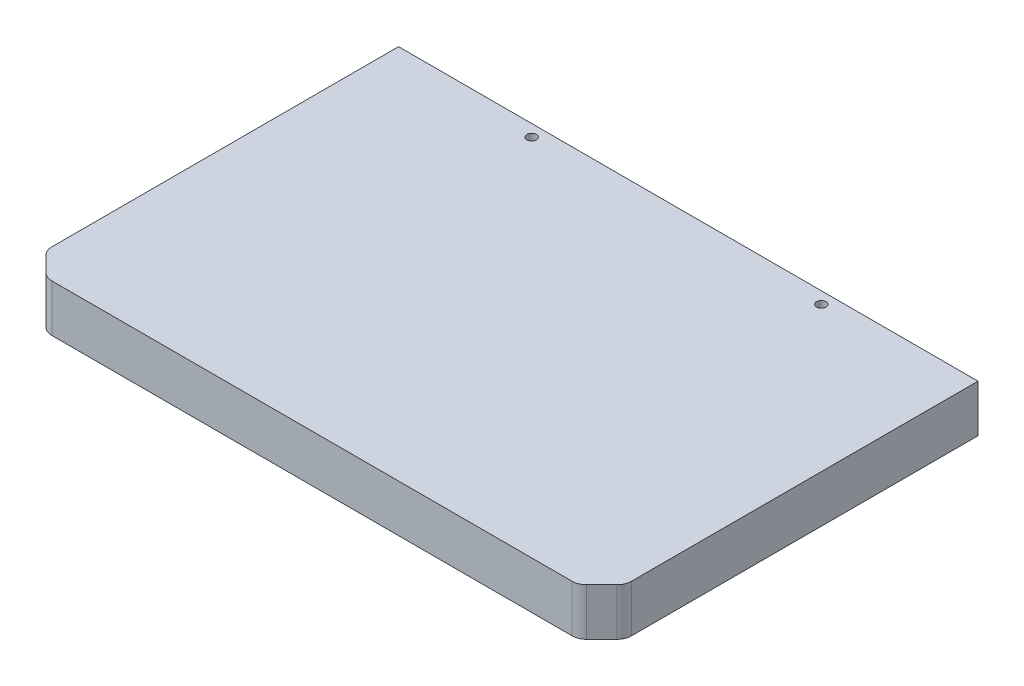
SolidWorks part; units mm, degrees
ref_plane "Front Plane" through (0, 0, 0) normal (0, 0, 1) x (1, 0, 0)
ref_plane "Top Plane" through (0, 0, 0) normal (0, 1, 0) x (1, 0, 0)
ref_plane "Right Plane" through (0, 0, 0) normal (1, 0, 0) x (0, 0, -1)
sketch "Sketch1" plane through (0, 0, 0) normal (0, 1, 0) x (1, 0, 0)
  line L0 (-61.25, 35.25) -> (-61.25, 44.29)
  line L1 (-61.25, 35.25) -> (61.25, 35.25)
  line L2 (-61.25, 35.25) -> (-61.25, -35.25)
  line L3 (-61.25, -35.25) -> (61.25, -35.25)
  line L4 (61.25, 35.25) -> (61.25, -35.25)
  line L5 (-61.25, 35.25) -> (61.25, -35.25) construction
  line L6 (-61.25, -35.25) -> (61.25, 35.25) construction
  line L7 (-61.25, 44.29) -> (61.25, 44.29)
  line L8 (61.25, 44.29) -> (61.25, 35.25)
  line L9 (-61.25, 41.79) -> (-30.625, 41.79) construction
  line L10 (-30.625, 41.79) -> (0, 41.79) construction
  line L11 (0, 41.79) -> (30.625, 41.79) construction
  line L12 (30.625, 41.79) -> (61.25, 41.79) construction
  circle A0 centre (-30.625, 41.79) radius 1
  circle A1 centre (30.625, 41.79) radius 1
  point P0 (0, 0)
  dimension "D5" = 2
  dimension "D1" = 122.5
  dimension "D2" = 70.5
  dimension "D3" = 6.54
  dimension "D4" = 2.5
sketch "Sketch2" plane through (0, 0, 0) normal (0, 1, 0) x (1, 0, 0)
  line L0 (-61.25, 44.29) -> (-61.25, -29.0074)
  line L1 (-55.0074, -35.25) -> (55.0074, -35.25)
  line L2 (61.25, -29.0074) -> (61.25, 44.29)
  line L3 (61.25, 44.29) -> (-61.25, 44.29)
  line L4 (57.1287, -34.3713) -> (60.3713, -31.1287)
  line L5 (-60.3713, -31.1287) -> (-57.1287, -34.3713)
  circle A0 centre (-30.625, 41.79) radius 1
  circle A1 centre (-30.625, 41.79) radius 1 construction
  circle A2 centre (30.625, 41.79) radius 1
  circle A3 centre (30.625, 41.79) radius 1 construction
  arc A4 (57.1287, -34.3713) -> (55.0074, -35.25) centre (55.0074, -32.25) cw
  arc A5 (60.3713, -31.1287) -> (61.25, -29.0074) centre (58.25, -29.0074) ccw
  arc A6 (-57.1287, -34.3713) -> (-55.0074, -35.25) centre (-55.0074, -32.25) ccw
  arc A7 (-60.3713, -31.1287) -> (-61.25, -29.0074) centre (-58.25, -29.0074) cw
  point P1 (-61.25, -35.25)
  point P4 (61.25, -35.25)
  point P22 (56.25, -35.25)
  point P25 (61.25, -30.25)
  point P28 (-56.25, -35.25)
  point P31 (-61.25, -30.25)
  dimension "D1" = 3
extrude "Boss-Extrude1" add sketch "Sketch2" along normal blind 10
